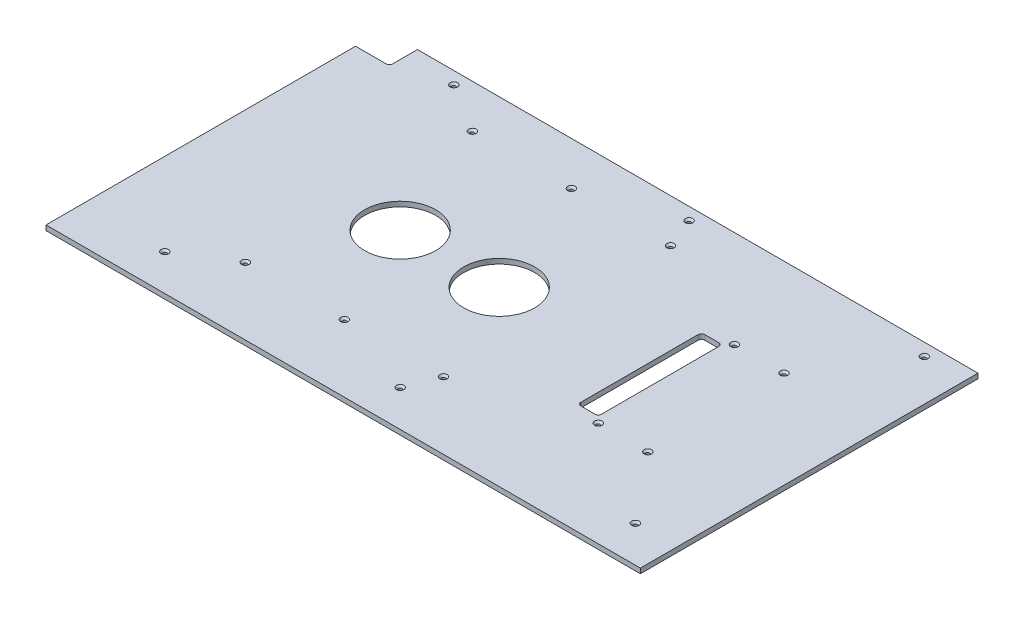
SolidWorks part; units mm, degrees
ref_plane "Front Plane" through (0, 0, 0) normal (0, 0, 1) x (1, 0, 0)
ref_plane "Top Plane" through (0, 0, 0) normal (0, 1, 0) x (1, 0, 0)
ref_plane "Right Plane" through (0, 0, 0) normal (1, 0, 0) x (0, 0, -1)
sketch "Sketch1" plane through (0, 0, 0) normal (0, 1, 0) x (1, 0, 0)
  line L0 (-360, 204.5) -> (360, -204.5) construction
  line L1 (-360, 204.5) -> (360, 204.5)
  line L2 (-360, 204.5) -> (-360, -204.5)
  line L3 (-360, -204.5) -> (360, -204.5)
  line L4 (360, 204.5) -> (360, -204.5)
  dimension "D1" = 409
  dimension "D2" = 720
extrude "Boss-Extrude1" add sketch "Sketch1" along normal mid plane 6
sketch "Sketch5" plane through (0, 3, 0) normal (0, 1, 0) x (1, 0, 0)
  line L0 (0, 4.5) -> (150, 4.5) construction
  line L1 (154, 79.5) -> (171, 79.5)
  line L2 (150, 75.5) -> (150, -66.5)
  line L3 (154, -70.5) -> (171, -70.5)
  line L4 (175, 75.5) -> (175, -66.5)
  line L6 (360, 204.5) -> (-360, 204.5) construction
  line L7 (360, -204.5) -> (360, 204.5) construction
  arc A0 (171, 79.5) -> (175, 75.5) centre (171, 75.5) cw
  arc A1 (150, -66.5) -> (154, -70.5) centre (154, -66.5) ccw
  arc A2 (171, -70.5) -> (175, -66.5) centre (171, -66.5) ccw
  arc A3 (154, 79.5) -> (150, 75.5) centre (154, 75.5) ccw
  point P12 (175, 79.5)
  point P15 (150, -70.5)
  point P20 (150, 79.5)
  dimension "D6" = 4
  dimension "D1" = 25
  dimension "D2" = 150
  dimension "D3" = 150
  dimension "D4" = 200
  dimension "D5" = 185
extrude "Cut-Extrude2" cut sketch "Sketch5" against normal through all
sketch "Sketch6" plane through (0, 3, 0) normal (0, 1, 0) x (1, 0, 0)
  line L1 (-360, 204.5) -> (-319, 204.5)
  line L2 (-360, 204.5) -> (-360, 170.5)
  line L3 (-360, 170.5) -> (-323, 170.5)
  line L4 (-319, 204.5) -> (-319, 174.5)
  arc A0 (-323, 170.5) -> (-319, 174.5) centre (-323, 174.5) ccw
  dimension "D3" = 4
  dimension "D1" = 34
  dimension "D2" = 41
extrude "Cut-Extrude3" cut sketch "Sketch6" against normal through all
sketch "Sketch7" plane through (0, 3, 0) normal (0, 1, 0) x (1, 0, 0)
  line L0 (-302.3097, 14.5) -> (-189.8341, 14.5) construction
  line L1 (-260, 189.5) -> (25, 189.5) construction
  line L2 (25, 189.5) -> (310, 189.5) construction
  line L3 (25, 189.5) -> (25, 204.5) construction
  line L4 (-80, 152) -> (-80, -123) construction
  line L5 (25, -160.5) -> (25, -204.5) construction
  line L6 (182.5, 87) -> (182.5, -78) construction
  line L7 (182.5, -78) -> (242.5, -78) construction
  line L8 (242.5, -78) -> (242.5, 87) construction
  line L9 (-200, -123) -> (-200, 152) construction
  line L10 (-200, -123) -> (-80, -123) construction
  line L11 (360, 204.5) -> (-319, 204.5) construction
  line L12 (-360, 170.5) -> (-360, -204.5) construction
  line L13 (360, -204.5) -> (360, 204.5) construction
  line L14 (-360, -204.5) -> (360, -204.5) construction
  line L15 (242.5, 87) -> (182.5, 87) construction
  line L16 (175, 4.5) -> (182.5, 4.5) construction
  line L17 (175, -66.5) -> (175, 75.5) construction
  circle A0 centre (-260, 189.5) radius 2.25
  circle A1 centre (25, 189.5) radius 2.25
  circle A2 centre (310, 189.5) radius 2.25
  circle A3 centre (310, -160.5) radius 2.25
  circle A4 centre (25, -160.5) radius 2.25
  circle A5 centre (-260, -160.5) radius 2.25
  circle A6 centre (-200, 152) radius 2.25
  circle A7 centre (-200, -123) radius 2.25
  circle A8 centre (-80, 152) radius 2.25
  circle A9 centre (-80, -123) radius 2.25
  circle A10 centre (40, 152) radius 2.25
  circle A11 centre (40, -123) radius 2.25
  circle A12 centre (182.5, 87) radius 2.25
  circle A13 centre (242.5, 87) radius 2.25
  circle A14 centre (242.5, -78) radius 2.25
  circle A15 centre (182.5, -78) radius 2.25
  dimension "D1" = 4.5
  dimension "D6" = 81.5
  dimension "D5" = 50
  dimension "D11" = 7.5
  dimension "D2" = 44
  dimension "D3" = 15
  dimension "D4" = 100
  dimension "D7" = 52.5
  dimension "D8" = 280
  dimension "D10" = 120
  dimension "D12" = 60
  dimension "D13" = 165
  dimension "D9" = 3
extrude "Cut-Extrude4" cut sketch "Sketch7" against normal through all
sketch "Sketch8" plane through (0, 3, 0) normal (0, 1, 0) x (1, 0, 0)
  circle A0 centre (-260, 189.5) radius 4.5
  circle A1 centre (-200, 152) radius 4.5
  circle A2 centre (-80, 152) radius 4.5
  circle A3 centre (25, 189.5) radius 4.5
  circle A4 centre (40, 152) radius 4.5
  circle A5 centre (310, 189.5) radius 4.5
  circle A6 centre (-200, -123) radius 4.5
  circle A7 centre (-260, -160.5) radius 4.5
  circle A8 centre (-80, -123) radius 4.5
  circle A9 centre (25, -160.5) radius 4.5
  circle A10 centre (40, -123) radius 4.5
  circle A11 centre (310, -160.5) radius 4.5
  circle A12 centre (182.5, 87) radius 4.5
  circle A13 centre (242.5, 87) radius 4.5
  circle A14 centre (182.5, -78) radius 4.5
  circle A15 centre (242.5, -78) radius 4.5
  dimension "D1" = 9
extrude "Cut-Extrude5" cut sketch "Sketch8" against normal through all draft 45
sketch "Sketch9" plane through (0, 3, 0) normal (0, 1, 0) x (1, 0, 0)
  line L0 (-140, 4.5) -> (-20, 4.5) construction
  line L1 (-20, 4.5) -> (150, 4.5) construction
  line L2 (150, 75.5) -> (150, -66.5) construction
  line L3 (-80, 4.5) -> (-80, 152) construction
  circle A0 centre (-20, 4.5) radius 43
  circle A1 centre (-140, 4.5) radius 43
  dimension "D1" = 86
  dimension "D2" = 120
extrude "Cut-Extrude6" cut sketch "Sketch9" against normal through all
